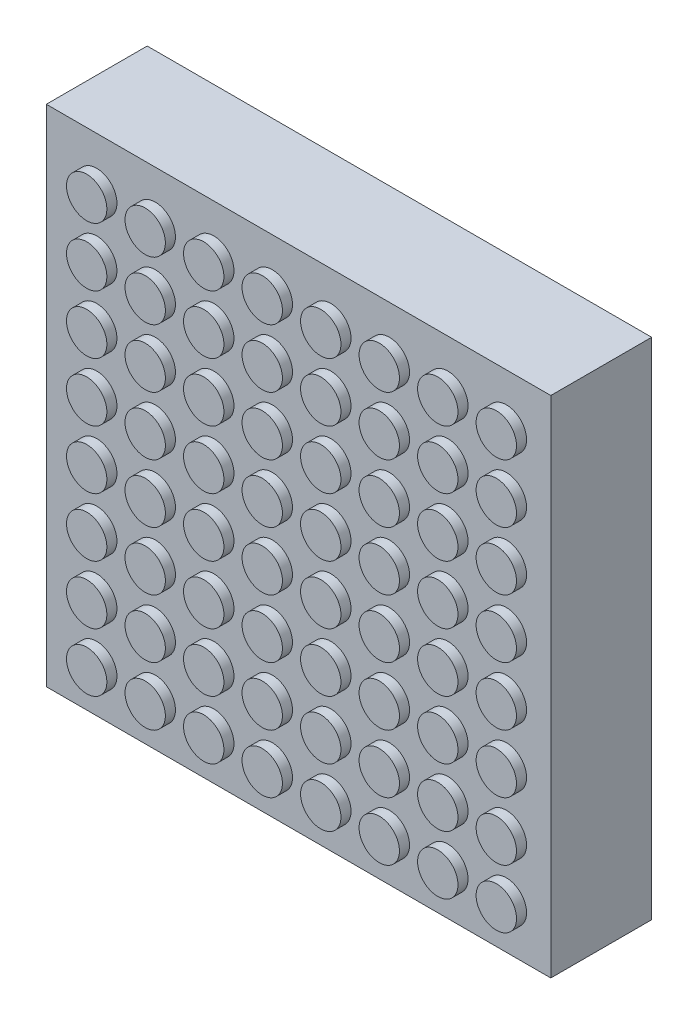
SolidWorks part; units mm, degrees
ref_plane "前基準面" through (0, 0, 0) normal (0, 0, 1) x (1, 0, 0)
ref_plane "上基準面" through (0, 0, 0) normal (0, 1, 0) x (1, 0, 0)
ref_plane "右基準面" through (0, 0, 0) normal (1, 0, 0) x (0, 0, -1)
sketch "草圖1" plane through (0, 0, 0) normal (0, 0, 1) x (1, 0, 0)
  line L1 (0, 0) -> (50, 0)
  line L2 (0, 0) -> (0, 50)
  line L3 (0, 50) -> (50, 50)
  line L4 (50, 0) -> (50, 50)
  dimension "D1" = 50
  dimension "D2" = 50
extrude "填料-伸長1" add sketch "草圖1" along normal blind 10
sketch "草圖2" plane through (0, 0, 10) normal (0, 0, 1) x (1, 0, 0)
  line L0 (50, 50) -> (0, 50) construction
  line L1 (0, 50) -> (0, 0) construction
  circle A0 centre (5, 45) radius 2
  circle A1 centre (10.8, 45) radius 2
  circle A2 centre (16.6, 45) radius 2
  circle A3 centre (22.4, 45) radius 2
  circle A4 centre (28.2, 45) radius 2
  circle A5 centre (34, 45) radius 2
  circle A6 centre (39.8, 45) radius 2
  circle A7 centre (45.6, 45) radius 2
  circle A8 centre (5, 39.2) radius 2
  circle A9 centre (10.8, 39.2) radius 2
  circle A10 centre (16.6, 39.2) radius 2
  circle A11 centre (22.4, 39.2) radius 2
  circle A12 centre (28.2, 39.2) radius 2
  circle A13 centre (34, 39.2) radius 2
  circle A14 centre (39.8, 39.2) radius 2
  circle A15 centre (45.6, 39.2) radius 2
  circle A16 centre (5, 33.4) radius 2
  circle A17 centre (10.8, 33.4) radius 2
  circle A18 centre (16.6, 33.4) radius 2
  circle A19 centre (22.4, 33.4) radius 2
  circle A20 centre (28.2, 33.4) radius 2
  circle A21 centre (34, 33.4) radius 2
  circle A22 centre (39.8, 33.4) radius 2
  circle A23 centre (45.6, 33.4) radius 2
  circle A24 centre (5, 27.6) radius 2
  circle A25 centre (10.8, 27.6) radius 2
  circle A26 centre (16.6, 27.6) radius 2
  circle A27 centre (22.4, 27.6) radius 2
  circle A28 centre (28.2, 27.6) radius 2
  circle A29 centre (34, 27.6) radius 2
  circle A30 centre (39.8, 27.6) radius 2
  circle A31 centre (45.6, 27.6) radius 2
  circle A32 centre (5, 21.8) radius 2
  circle A33 centre (10.8, 21.8) radius 2
  circle A34 centre (16.6, 21.8) radius 2
  circle A35 centre (22.4, 21.8) radius 2
  circle A36 centre (28.2, 21.8) radius 2
  circle A37 centre (34, 21.8) radius 2
  circle A38 centre (39.8, 21.8) radius 2
  circle A39 centre (45.6, 21.8) radius 2
  circle A40 centre (5, 16) radius 2
  circle A41 centre (10.8, 16) radius 2
  circle A42 centre (16.6, 16) radius 2
  circle A43 centre (22.4, 16) radius 2
  circle A44 centre (28.2, 16) radius 2
  circle A45 centre (34, 16) radius 2
  circle A46 centre (39.8, 16) radius 2
  circle A47 centre (45.6, 16) radius 2
  circle A48 centre (5, 10.2) radius 2
  circle A49 centre (10.8, 10.2) radius 2
  circle A50 centre (16.6, 10.2) radius 2
  circle A51 centre (22.4, 10.2) radius 2
  circle A52 centre (28.2, 10.2) radius 2
  circle A53 centre (34, 10.2) radius 2
  circle A54 centre (39.8, 10.2) radius 2
  circle A55 centre (45.6, 10.2) radius 2
  circle A56 centre (5, 4.4) radius 2
  circle A57 centre (10.8, 4.4) radius 2
  circle A58 centre (16.6, 4.4) radius 2
  circle A59 centre (22.4, 4.4) radius 2
  circle A60 centre (28.2, 4.4) radius 2
  circle A61 centre (34, 4.4) radius 2
  circle A62 centre (39.8, 4.4) radius 2
  circle A63 centre (45.6, 4.4) radius 2
  dimension "D1" = 5
  dimension "D2" = 5
  dimension "D3" = 4
  dimension "D5" = 5.8
  dimension "D4" = 8
  dimension "D6" = 8
extrude "填料-伸長2" add sketch "草圖2" along normal blind 1
